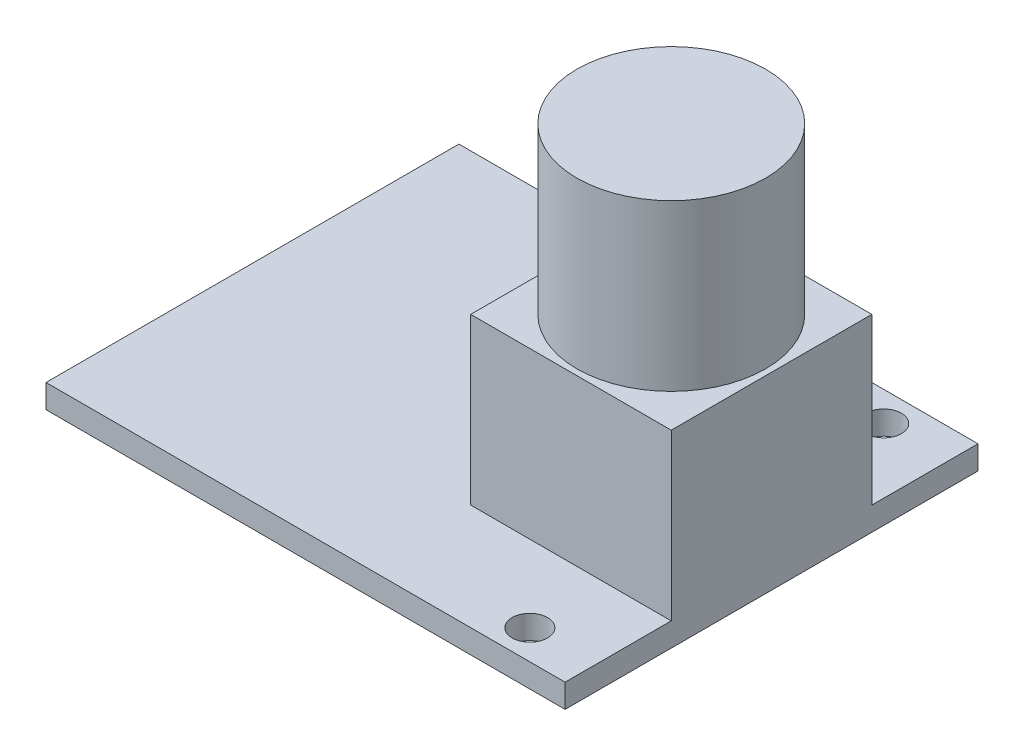
SolidWorks part; units mm, degrees
ref_plane "Front Plane" through (0, 0, 0) normal (0, 0, 1) x (1, 0, 0)
ref_plane "Top Plane" through (0, 0, 0) normal (0, 1, 0) x (1, 0, 0)
ref_plane "Right Plane" through (0, 0, 0) normal (1, 0, 0) x (0, 0, -1)
sketch "草图1" plane through (0, 0, 0) normal (0, 1, 0) x (1, 0, 0)
  line L1 (-22, 17.5) -> (22, 17.5)
  line L2 (-22, 17.5) -> (-22, -17.5)
  line L3 (-22, -17.5) -> (22, -17.5)
  line L4 (22, 17.5) -> (22, -17.5)
  line L5 (-22, 17.5) -> (22, -17.5) construction
  line L6 (-22, -17.5) -> (22, 17.5) construction
  point P0 (0, 0)
  dimension "D1" = 35
  dimension "D2" = 44
extrude "凸台-拉伸1" add sketch "草图1" along normal blind 2
sketch "草图2" plane through (0, 2, 0) normal (0, 1, 0) x (1, 0, 0)
  line L0 (0, 0) -> (22, 0) construction
  line L1 (22, -17.5) -> (22, 17.5) construction
  line L3 (5, 8.5) -> (22, 8.5)
  line L4 (5, 8.5) -> (5, -8.5)
  line L5 (5, -8.5) -> (22, -8.5)
  line L6 (22, 8.5) -> (22, -8.5)
  line L7 (5, 8.5) -> (22, -8.5) construction
  line L8 (5, -8.5) -> (22, 8.5) construction
  circle A0 centre (13.5, 0) radius 7.8393
  point P5 (13.5, 0)
  dimension "D1" = 17
  dimension "D2" = 17
extrude "凸台-拉伸2" add sketch "草图2" along normal blind 14 contours L4 L3 L6 L5
sketch "草图3" plane through (0, 16, 0) normal (0, 1, 0) x (1, 0, 0)
  line L0 (5, 8.5) -> (22, -8.5) construction
  circle A0 centre (13.5, 0) radius 8
  dimension "D1" = 16
extrude "凸台-拉伸3" add sketch "草图3" along normal blind 14
sketch "草图4" plane through (0, 0, 0) normal (0, -1, 0) x (1, 0, 0)
  line L0 (0, 0) -> (36.3639, 0) construction
  circle A0 centre (16.5116, -15) radius 1.5
  circle A1 centre (16.5116, 15) radius 1.5
  dimension "D1" = 3
  dimension "D2" = 15
extrude "切除-拉伸1" cut sketch "草图4" against normal blind 10
ref_plane "基准面1" through (13.5, 0, 0) normal (1, 0, 0) x (0, 0, -1)
